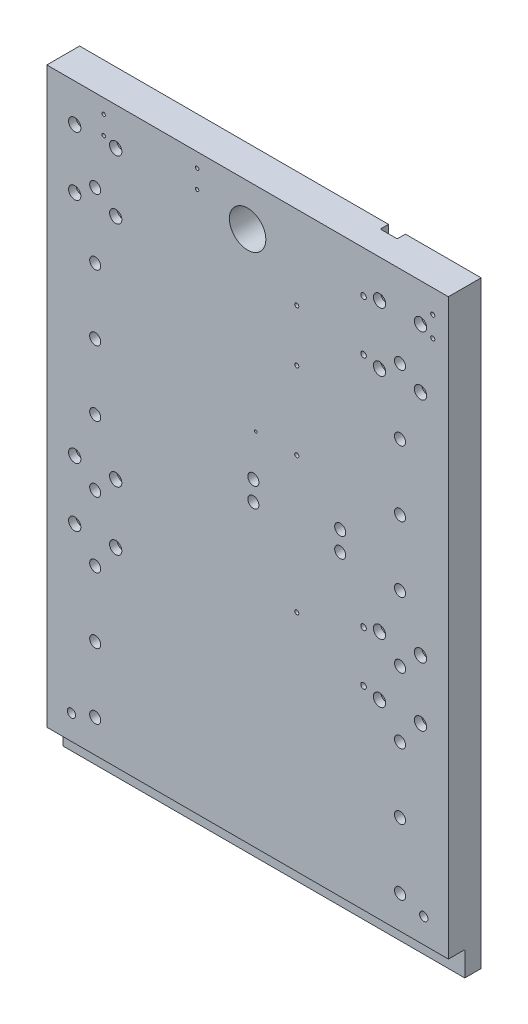
SolidWorks part; units mm, degrees
material "Low Carbon Steel"
ref_plane "Front Plane" through (0, 0, 0) normal (0, 0, 1) x (1, 0, 0)
ref_plane "Top Plane" through (0, 0, 0) normal (0, 1, 0) x (1, 0, 0)
ref_plane "Right Plane" through (0, 0, 0) normal (1, 0, 0) x (0, 0, -1)
sketch "Sketch1" plane through (0, 0, 0) normal (0, 0, 1) x (1, 0, 0)
  line L0 (-245, 365) -> (245, -365) construction
  line L1 (-245, -365) -> (245, -365)
  line L2 (-245, -365) -> (-245, 365)
  line L3 (-245, 365) -> (245, 365)
  line L4 (245, -365) -> (245, 365)
  dimension "D1" = 490
  dimension "D2" = 730
extrude "Boss-Extrude1" add sketch "Sketch1" along normal blind 50.8
sketch "Sketch3" plane through (-245, 0, 0) normal (-1, 0, 0) x (0, 0, 1)
  line L0 (50.8, -365) -> (0, -365) construction
  line L1 (0, 365) -> (5, 365)
  line L2 (0, 365) -> (0, -365)
  line L3 (0, -365) -> (5, -365)
  line L4 (5, 365) -> (5, -365)
  line L5 (45, -335) -> (25, -335)
  line L6 (50.8, 365) -> (45, 365)
  line L7 (50.8, 365) -> (50.8, -365)
  line L8 (50.8, -365) -> (25, -365)
  line L9 (45, 365) -> (45, -335)
  line L10 (25, -335) -> (25, -365)
  dimension "D1" = 5
  dimension "D2" = 40
  dimension "D3" = 20
  dimension "D4" = 30
extrude "Cut-Extrude1" cut sketch "Sketch3" against normal through all
hole_wizard "M5 Tapped Hole1" positions "Sketch5" profile "Sketch4" tap size "M5" standard "Peddi DIN"
sketch "Sketch5" plane through (0, 0, 45) normal (0, 0, 1) x (1, 0, 0)
  line L0 (-175.625, 347.5) -> (-61.625, 347.5) construction
  line L1 (-61.625, 347.5) -> (-61.625, 325) construction
  line L2 (-61.625, 325) -> (-175.625, 325) construction
  line L3 (-175.625, 325) -> (-175.625, 347.5) construction
  line L5 (245, -335) -> (-245, -335) construction
  point P0 (-175.625, 347.5)
  point P2 (-61.625, 347.5)
  point P4 (-61.625, 325)
  point P6 (-175.625, 325)
  dimension "D1" = 114
  dimension "D2" = 22.5
  dimension "D3" = 660
  dimension "D4" = 61.625
sketch "Sketch4" plane through (-175.625, 347.5, 45) normal (1, 0, 0) x (0, -1, 0)
  line L0 (0, 0) -> (0, 24.7618)
  line L1 (0, 24.7618) -> (2.1, 23.5)
  line L2 (2.1, 23.5) -> (2.1, 0)
  line L5 (2.1, 0) -> (0, 0)
  line L10 (0, 24.7618) -> (-2.1, 23.5) construction
  line L11 (0, -6.35) -> (0, 107.95) construction
  dimension "Tap Drill Dia." = 4.2
  dimension "Tap Drill Depth" = 23.5
  dimension "Drill Angle" = 118
cosmetic thread "Hole Thread5" parameters "D1"=12.5, "D2"=5
cosmetic thread "Hole Thread6" parameters "D1"=12.5, "D2"=5
cosmetic thread "Hole Thread7" parameters "D1"=12.5, "D2"=5
cosmetic thread "Hole Thread8" parameters "D1"=12.5, "D2"=5
hole_wizard "M12 Clearance Hole1" positions "Sketch7" profile "Sketch6" hole size "M12" standard "Peddi DIN" end condition through all
sketch "Sketch7" plane through (0, 0, 5) normal (0, 0, -1) x (-1, 0, 0)
  line L0 (-113, 29) -> (-7, 29) construction
  line L1 (-7, 29) -> (-7, 53) construction
  line L2 (-7, 53) -> (-113, 53) construction
  line L3 (-113, 53) -> (-113, 29) construction
  line L5 (-245, -335) -> (245, -335) construction
  point P0 (-113, 53)
  point P2 (-7, 53)
  point P4 (-7, 29)
  point P6 (-113, 29)
  dimension "D1" = 364
  dimension "D2" = 24
  dimension "D3" = 106
  dimension "D4" = 113
sketch "Sketch6" plane through (113, 53, 5) normal (1, 0, 0) x (0, 1, 0)
  line L0 (0, 0) -> (0, 40)
  line L1 (0, 40) -> (6.75, 40)
  line L2 (6.75, 40) -> (6.75, 0)
  line L5 (6.75, 0) -> (0, 0)
  line L11 (0, -6.35) -> (0, 107.95) construction
  dimension "Thru Hole Dia." = 13.5
  dimension "Thru Hole Depth" = 40
sketch "Sketch8" plane through (0, 0, 5) normal (0, 0, -1) x (-1, 0, 0)
  line L0 (-82.5, 41) -> (-37.5, 41) construction
  line L1 (-82.5, 47) -> (-37.5, 47)
  line L2 (-82.5, 35) -> (-37.5, 35)
  line L3 (-113, 53) -> (-7, 29) construction
  arc A0 (-82.5, 47) -> (-82.5, 35) centre (-82.5, 41) ccw
  arc A1 (-37.5, 35) -> (-37.5, 47) centre (-37.5, 41) ccw
  point P2 (-60, 41)
  dimension "D1" = 12
  dimension "D2" = 45
extrude "Cut-Extrude2" cut sketch "Sketch8" against normal blind 5.08
hole_wizard "CBORE for M12 Hex Socket Head Cap Screw1" positions "Sketch9" profile "Sketch10" counterbore size "M12" standard "Peddi DIN" end condition through all
sketch "Sketch9" plane through (0, 0, 5) normal (0, 0, -1) x (-1, 0, 0)
  line L0 (-186, -295) -> (186, -295) construction
  line L3 (0, -295) -> (0, 0) construction
  line L5 (-245, -365) -> (245, -365) construction
  point P1 (-186, -295)
  point P2 (186, -295)
  dimension "D1" = 372
  dimension "D2" = 70
sketch "Sketch10" plane through (186, -295, 5) normal (1, 0, 0) x (0, 1, 0)
  line L0 (0, 0) -> (0, 40)
  line L1 (0, 40) -> (6.75, 40)
  line L3 (6.75, 40) -> (6.75, 13)
  line L4 (6.75, 13) -> (10, 13)
  line L5 (10, 13) -> (10, 0)
  line L7 (10, 0) -> (0, 0)
  line L11 (0, -6.35) -> (0, 107.95) construction
  dimension "Thru Hole Dia." = 13.5
  dimension "Thru Hole Depth" = 40
  dimension "C'Bore Dia." = 20
  dimension "C'Bore Depth" = 13
pattern_linear "LPattern1" count 8 spacing 80 along (0, 1, 0) of "CBORE for M12 Hex Socket Head Cap Screw1"
hole_wizard "CBORE for M8 Hex Socket Head Cap Screw1" positions "Sketch11" profile "Sketch12" counterbore size "M8" standard "Peddi DIN" end condition through all
sketch "Sketch11" plane through (0, 0, 45) normal (0, 0, 1) x (1, 0, 0)
  line L1 (211, 319) -> (161, 319) construction
  line L2 (211, 319) -> (211, 247) construction
  line L3 (211, 247) -> (161, 247) construction
  line L4 (161, 319) -> (161, 247) construction
  line L6 (186, 283) -> (-186, 283) construction
  line L7 (186, 283) -> (186, -67) construction
  line L8 (186, -67) -> (-186, -67) construction
  line L9 (-186, 283) -> (-186, -67) construction
  line L10 (186, 319) -> (186, 247) construction
  line L15 (0, -67) -> (0, 0) construction
  line L18 (245, -335) -> (-245, -335) construction
  point P0 (211, 319)
  dimension "D1" = 50
  dimension "D2" = 72
  dimension "D3" = 372
  dimension "D4" = 350
  dimension "D5" = 618
sketch "Sketch12" plane through (211, 319, 45) normal (1, 0, 0) x (0, -1, 0)
  line L0 (0, 0) -> (0, 40)
  line L1 (0, 40) -> (4.5, 40)
  line L3 (4.5, 40) -> (4.5, 9)
  line L4 (4.5, 9) -> (7.5, 9)
  line L5 (7.5, 9) -> (7.5, 0)
  line L7 (7.5, 0) -> (0, 0)
  line L11 (0, -6.35) -> (0, 107.95) construction
  dimension "Thru Hole Dia." = 9
  dimension "Thru Hole Depth" = 40
  dimension "C'Bore Dia." = 15
  dimension "C'Bore Depth" = 9
pattern_linear "LPattern2" count 2 spacing 50 along (-1, 0, 0) count 2 spacing 72 along (0, -1, 0) of "CBORE for M8 Hex Socket Head Cap Screw1"
pattern_linear "LPattern5" count 2 spacing 372 along (-1, 0, 0) count 2 spacing 350 along (0, -1, 0) of "LPattern2", "CBORE for M8 Hex Socket Head Cap Screw1"
hole_wizard "M6 Tapped Hole1" positions "Sketch13" profile "Sketch14" tap size "M6" standard "Peddi DIN"
sketch "Sketch13" plane through (0, 0, 45) normal (0, 0, 1) x (1, 0, 0)
  line L0 (245, 365) -> (245, -335) construction
  line L1 (245, 365) -> (-245, 365) construction
  point P0 (225.95, 336.5)
  point P2 (225.95, 311.5)
  dimension "D1" = 25
  dimension "D2" = 19.05
  dimension "D3" = 28.5
sketch "Sketch14" plane through (225.95, 336.5, 45) normal (1, 0, 0) x (0, -1, 0)
  line L0 (0, 0) -> (0, 29.4922)
  line L1 (0, 29.4922) -> (2.5, 27.99)
  line L2 (2.5, 27.99) -> (2.5, 0)
  line L5 (2.5, 0) -> (0, 0)
  line L10 (0, 29.4922) -> (-2.5, 27.99) construction
  line L11 (0, -6.35) -> (0, 107.95) construction
  dimension "Tap Drill Dia." = 5
  dimension "Tap Drill Depth" = 27.99
  dimension "Drill Angle" = 118
cosmetic thread "Hole Thread9" parameters "D1"=15.01, "D2"=6
cosmetic thread "Hole Thread10" parameters "D1"=15.01, "D2"=6
hole_wizard "M6 Tapped Hole2" positions "Sketch15" profile "Sketch16" tap size "M6" standard "Peddi DIN"
sketch "Sketch15" plane through (0, 0, 45) normal (0, 0, 1) x (1, 0, 0)
  line L0 (7, 53) -> (113, 53) construction
  line L3 (60, 53) -> (60, 105) construction
  line L5 (245, 365) -> (-245, 365) construction
  point P0 (60, 105)
  point P2 (60, -61)
  point P19 (60, 263.4)
  point P21 (60, 199.9)
  dimension "D1" = 166
  dimension "D2" = 260
  dimension "D3" = 63.5
  dimension "D4" = 101.6
sketch "Sketch16" plane through (60, 105, 45) normal (1, 0, 0) x (0, -1, 0)
  line L0 (0, 0) -> (0, 29.4922)
  line L1 (0, 29.4922) -> (2.5, 27.99)
  line L2 (2.5, 27.99) -> (2.5, 0)
  line L5 (2.5, 0) -> (0, 0)
  line L10 (0, 29.4922) -> (-2.5, 27.99) construction
  line L11 (0, -6.35) -> (0, 107.95) construction
  dimension "Tap Drill Dia." = 5
  dimension "Tap Drill Depth" = 27.99
  dimension "Drill Angle" = 118
cosmetic thread "Hole Thread11" parameters "D1"=15.01, "D2"=6
cosmetic thread "Hole Thread12" parameters "D1"=15.01, "D2"=6
cosmetic thread "Hole Thread13" parameters "D1"=15.01, "D2"=6
cosmetic thread "Hole Thread14" parameters "D1"=15.01, "D2"=6
sketch "Sketch17" plane through (0, 0, 5) normal (0, 0, -1) x (-1, 0, 0)
  line L0 (-245, 365) -> (245, 365) construction
  line L1 (-152.5875, 365) -> (-131.95, 365)
  line L2 (-152.5875, 365) -> (-152.5875, 222)
  line L3 (-152.5875, 222) -> (-131.95, 222) construction
  line L4 (-131.95, 365) -> (-131.95, 222)
  line L5 (-151, 365) -> (-151, 222) construction
  line L6 (-142.2687, -4.5) -> (-142.2687, -129.5) construction
  line L7 (-131.95, -4.5) -> (-131.95, -129.5)
  line L8 (-152.5875, -4.5) -> (-152.5875, -129.5)
  line L9 (-161, -31) -> (-161, -103) construction
  line L10 (-142.2687, -67) -> (-161, -67) construction
  arc A0 (-152.5875, 222) -> (-131.95, 222) centre (-142.2687, 222) ccw
  circle A1 centre (-161, 247) radius 4.5 construction
  arc A2 (-131.95, -4.5) -> (-152.5875, -4.5) centre (-142.2687, -4.5) ccw
  arc A3 (-152.5875, -129.5) -> (-131.95, -129.5) centre (-142.2687, -129.5) ccw
  point P11 (-142.2687, -67)
  dimension "D4" = 25
  dimension "D1" = 10
  dimension "D2" = 1.5875
  dimension "D3" = 19.05
  dimension "D5" = 125
extrude "Cut-Extrude3" cut sketch "Sketch17" against normal blind 10
fillet "Fillet1" radius 0.7937 7 edges at (142.2687, 5.8188, 15) (131.95, -67, 15) (142.2687, -139.8188, 15) (131.95, 293.5, 15) (142.2687, 211.6812, 15) (152.5875, -67, 15) (152.5875, 293.5, 15)
hole_wizard "M8 Tapped Hole1" positions "Sketch18" profile "Sketch19" tap size "M8" standard "Peddi DIN"
sketch "Sketch18" plane through (0, 0, 15) normal (0, 0, -1) x (-1, 0, 0)
  line L1 (-141.475, 314) -> (-141.475, 252) construction
  line L4 (-161, 319) -> (-161, 247) construction
  line L6 (-161, 283) -> (-141.475, 283) construction
  line L8 (-131.95, 365) -> (-131.95, 222) construction
  line L9 (-141.475, -36) -> (-141.475, -98) construction
  line L11 (-161, -31) -> (-161, -103) construction
  line L13 (-161, -67) -> (-141.475, -67) construction
  point P0 (-141.475, 314)
  point P2 (-141.475, 252)
  point P27 (-141.475, -36)
  point P28 (-141.475, -98)
  dimension "D1" = 62
  dimension "D2" = 9.525
sketch "Sketch19" plane through (141.475, 314, 15) normal (1, 0, 0) x (0, 1, 0)
  line L0 (0, 0) -> (0, 35.0329)
  line L1 (0, 35.0329) -> (3.4, 32.99)
  line L2 (3.4, 32.99) -> (3.4, 0)
  line L5 (3.4, 0) -> (0, 0)
  line L10 (0, 35.0329) -> (-3.4, 32.99) construction
  line L11 (0, -6.35) -> (0, 107.95) construction
  dimension "Tap Drill Dia." = 6.8
  dimension "Tap Drill Depth" = 32.99
  dimension "Drill Angle" = 118
cosmetic thread "Hole Thread15" parameters "D1"=19.99, "D2"=8
cosmetic thread "Hole Thread16" parameters "D1"=19.99, "D2"=8
cosmetic thread "Hole Thread17" parameters "D1"=19.99, "D2"=8
cosmetic thread "Hole Thread18" parameters "D1"=19.99, "D2"=8
fillet "Fillet2" radius 0.8128 1 edges at (0, -335, 25)
sketch "Sketch20" plane through (0, 0, 5) normal (0, 0, -1) x (-1, 0, 0)
  line L0 (-152.5875, -4.5) -> (-152.5875, -129.5) construction
  line L1 (147.9, 222.675) -> (224.1, 222.675)
  line L2 (147.9, 222.675) -> (147.9, 343.325)
  line L3 (147.9, 343.325) -> (224.1, 343.325)
  line L4 (224.1, 222.675) -> (224.1, 343.325)
  line L5 (224.1, -6.675) -> (147.9, -6.675)
  line L6 (224.1, -6.675) -> (224.1, -127.325)
  line L7 (224.1, -127.325) -> (147.9, -127.325)
  line L8 (147.9, -6.675) -> (147.9, -127.325)
  line L9 (-228.7875, -127.325) -> (-152.5875, -127.325)
  line L10 (-228.7875, -127.325) -> (-228.7875, -6.675)
  line L11 (-228.7875, -6.675) -> (-152.5875, -6.675)
  line L12 (-152.5875, -127.325) -> (-152.5875, -6.675)
  line L13 (-152.5875, 365) -> (-152.5875, 222) construction
  line L14 (-228.7875, 222.675) -> (-152.5875, 222.675)
  line L15 (-228.7875, 222.675) -> (-228.7875, 343.325)
  line L16 (-228.7875, 343.325) -> (-152.5875, 343.325)
  line L17 (-152.5875, 222.675) -> (-152.5875, 343.325)
  line L18 (211, -31) -> (161, -103) construction
  line L19 (186, -67) -> (224.1, -127.325) construction
  line L20 (186, -67) -> (147.9, -6.675) construction
  line L21 (-211, 319) -> (-211, 247) construction
  line L22 (-211, 283) -> (-228.7875, 283) construction
  dimension "D1" = 76.2
  dimension "D2" = 120.65
sketch "Sketch21" plane through (0, 0, 45) normal (0, 0, 1) x (1, 0, 0)
  line L0 (245, 365) -> (-245, 365) construction
  line L1 (-201.93, 365) -> (-170.18, 365)
  line L2 (-201.93, 365) -> (-201.93, -335)
  line L3 (-201.93, -335) -> (-170.18, -335)
  line L4 (-170.18, 365) -> (-170.18, -335)
  line L5 (245, -335) -> (-245, -335) construction
  line L6 (-245, -335) -> (245, -335) construction
  line L7 (170.18, -335) -> (201.93, -335)
  line L8 (170.18, -335) -> (170.18, 365)
  line L9 (170.18, 365) -> (201.93, 365)
  line L10 (201.93, -335) -> (201.93, 365)
  dimension "D1" = 170.18
  dimension "D2" = 170.18
  dimension "D3" = 31.75
  dimension "D4" = 31.75
fillet "Fillet3" radius 0.7937 4 edges at (88.5, 41, 10.08) (60, 47, 10.08) (31.5, 41, 10.08) (60, 35, 10.08)
sketch "Sketch22" plane through (0, 0, 45) normal (0, 0, 1) x (1, 0, 0)
  line L0 (245, 365) -> (-245, 365) construction
  line L1 (0, 314) -> (0, 365) construction
  line L2 (141.475, 314) -> (0, 314) construction
  circle A0 centre (0, 314) radius 22.225
  dimension "D1" = 44.45
  dimension "D2" = 51
extrude "Cut-Extrude4" cut sketch "Sketch22" against normal through all
hole_wizard "M4 Tapped Hole1" positions "Sketch23" profile "Sketch24" tap size "M4" standard "Peddi DIN"
sketch "Sketch23" plane through (0, 0, 45) normal (0, 0, 1) x (1, 0, 0)
  line L0 (60, 105) -> (10, 105) construction
  point P0 (10, 105)
  dimension "D1" = 50
sketch "Sketch24" plane through (10, 105, 45) normal (1, 0, 0) x (0, -1, 0)
  line L0 (0, 0) -> (0, 14.5014)
  line L1 (0, 14.5014) -> (1.65, 13.51)
  line L2 (1.65, 13.51) -> (1.65, 0)
  line L5 (1.65, 0) -> (0, 0)
  line L10 (0, 14.5014) -> (-1.65, 13.51) construction
  line L11 (0, -6.35) -> (0, 107.95) construction
  dimension "Tap Drill Dia." = 3.3
  dimension "Tap Drill Depth" = 13.51
  dimension "Drill Angle" = 118
cosmetic thread "Hole Thread19" parameters "D1"=10.01, "D2"=4
hole_wizard "M12 Tapped Hole1" positions "Sketch25" profile "Sketch26" tap size "M12" standard "Peddi DIN"
sketch "Sketch25" plane through (0, 0, 5) normal (0, 0, -1) x (-1, 0, 0)
  line L0 (-245, -365) -> (245, -365) construction
  line L1 (245, -365) -> (245, 365) construction
  line L2 (-245, -365) -> (-245, 365) construction
  point P0 (215, -305)
  point P2 (-215, -305)
  dimension "D1" = 60
  dimension "D2" = 30
  dimension "D3" = 30
sketch "Sketch26" plane through (-215, -305, 5) normal (1, 0, 0) x (0, 1, 0)
  line L0 (0, 0) -> (0, 47.0544)
  line L1 (0, 47.0544) -> (5.1, 43.99)
  line L2 (5.1, 43.99) -> (5.1, 0)
  line L5 (5.1, 0) -> (0, 0)
  line L10 (0, 47.0544) -> (-5.1, 43.99) construction
  line L11 (0, -6.35) -> (0, 107.95) construction
  dimension "Tap Drill Dia." = 10.2
  dimension "Tap Drill Depth" = 43.99
  dimension "Drill Angle" = 118
cosmetic thread "Hole Thread20" parameters "D1"=30, "D2"=12
cosmetic thread "Hole Thread21" parameters "D1"=30, "D2"=12
other "Freeze***"
